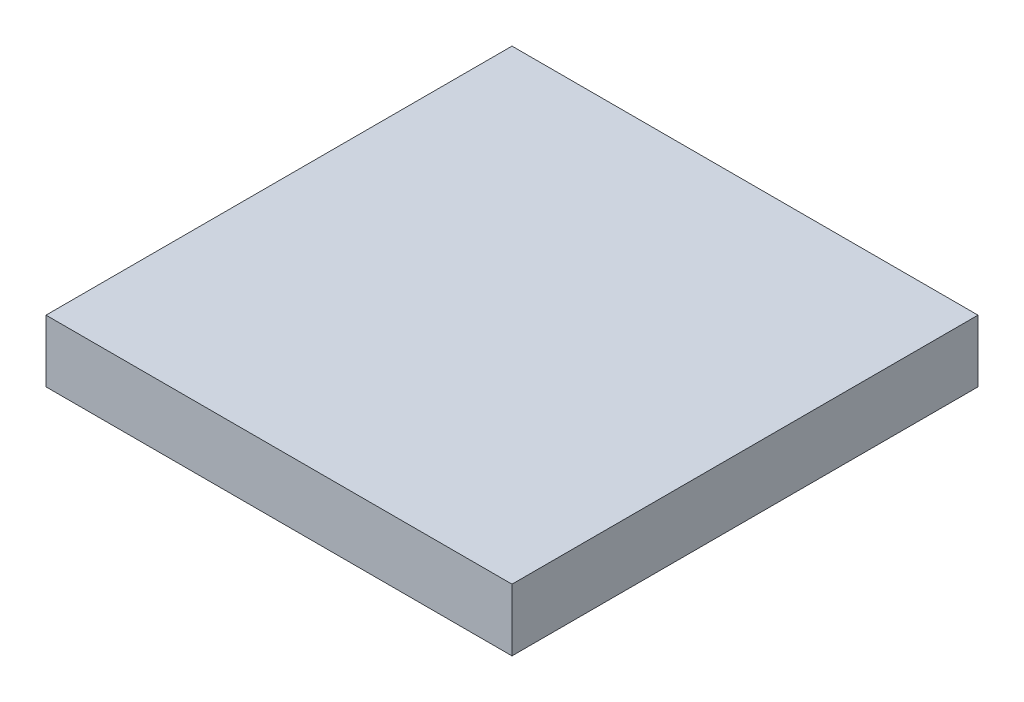
SolidWorks part; units mm, degrees
ref_plane "Front" through (0, 0, 0) normal (0, 0, 1) x (1, 0, 0)
ref_plane "Top" through (0, 0, 0) normal (0, 1, 0) x (1, 0, 0)
ref_plane "Right" through (0, 0, 0) normal (1, 0, 0) x (0, 0, -1)
sketch "Sketch1" plane through (0, 0, 0) normal (0, 1, 0) x (1, 0, 0)
  line L1 (-15, -15) -> (15, -15)
  line L2 (-15, -15) -> (-15, 15)
  line L3 (-15, 15) -> (15, 15)
  line L4 (15, -15) -> (15, 15)
  line L5 (-15, -15) -> (15, 15) construction
  line L6 (-15, 15) -> (15, -15) construction
  point P0 (0, 0)
  dimension "D1" = 30
  dimension "D2" = 30
extrude "Boss-Extrude1" add sketch "Sketch1" along normal mid plane 4
sketch "Sketch2" plane through (0, 2, 0) normal (0, 1, 0) x (1, 0, 0)
  circle A0 centre (30.9, 24) radius 4.25
  circle A1 centre (30.9, 24) radius 4 construction
  dimension "D1" = 8.5
extrude "Cut-Extrude1" cut sketch "Sketch2" against normal through all
